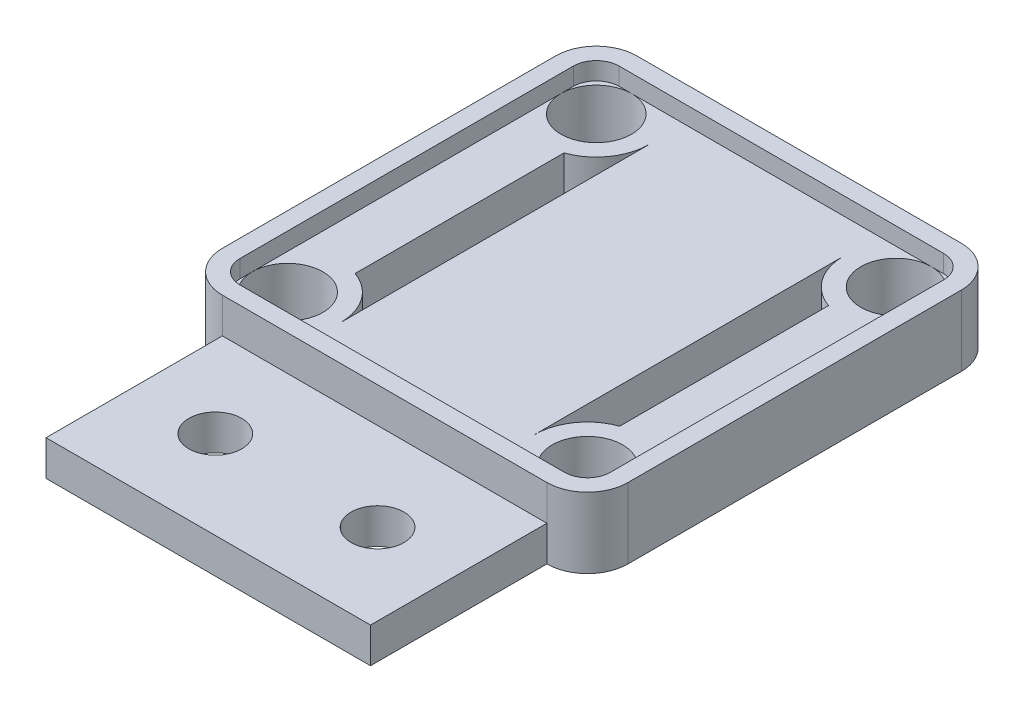
SolidWorks part; units mm, degrees
ref_plane "Front Plane" through (0, 0, 0) normal (0, 0, 1) x (1, 0, 0)
ref_plane "Top Plane" through (0, 0, 0) normal (0, 1, 0) x (1, 0, 0)
ref_plane "Right Plane" through (0, 0, 0) normal (1, 0, 0) x (0, 0, -1)
sketch "Sketch1" plane through (0, 0, 0) normal (0, 1, 0) x (1, 0, 0)
  line L1 (-12.6491, 14.6331) -> (5.7509, 14.6331)
  line L2 (-14.9491, 12.3331) -> (-14.9491, -6.5669)
  line L3 (-12.6491, -8.8669) -> (5.7509, -8.8669)
  line L4 (8.0509, 12.3331) -> (8.0509, -6.5669)
  line L5 (-14.9491, 14.6331) -> (8.0509, -8.8669) construction
  line L6 (-14.9491, -8.8669) -> (8.0509, 14.6331) construction
  arc A0 (8.0509, 12.3331) -> (5.7509, 14.6331) centre (5.7509, 12.3331) ccw
  arc A1 (-12.6491, -8.8669) -> (-14.9491, -6.5669) centre (-12.6491, -6.5669) cw
  arc A2 (5.7509, -8.8669) -> (8.0509, -6.5669) centre (5.7509, -6.5669) ccw
  arc A3 (-14.9491, 12.3331) -> (-12.6491, 14.6331) centre (-12.6491, 12.3331) cw
  point P0 (-3.4491, 2.8831)
  dimension "D3" = 2.3
  dimension "D4" = 2.3
  dimension "D1" = 23.5
  dimension "D2" = 23
extrude "Boss-Extrude1" add sketch "Sketch1" along normal blind 4
sketch "Sketch2" plane through (0, 4, 0) normal (0, 1, 0) x (1, 0, 0)
  line L8 (5.7509, 13.6331) -> (-12.6491, 13.6331)
  line L9 (-13.9491, 12.3331) -> (-13.9491, -6.5669)
  line L10 (-12.6491, -7.8669) -> (5.7509, -7.8669)
  line L11 (7.0509, -6.5669) -> (7.0509, 12.3331)
  line L12 (5.7509, 13.6331) -> (-12.6491, 13.6331)
  line L13 (-13.9491, 12.3331) -> (-13.9491, -6.5669)
  line L14 (-12.6491, -7.8669) -> (5.7509, -7.8669)
  line L15 (7.0509, -6.5669) -> (7.0509, 12.3331)
  arc A8 (7.0509, 12.3331) -> (5.7509, 13.6331) centre (5.7509, 12.3331) ccw
  arc A9 (-12.6491, 13.6331) -> (-13.9491, 12.3331) centre (-12.6491, 12.3331) ccw
  arc A10 (-13.9491, -6.5669) -> (-12.6491, -7.8669) centre (-12.6491, -6.5669) ccw
  arc A11 (5.7509, -7.8669) -> (7.0509, -6.5669) centre (5.7509, -6.5669) ccw
  arc A12 (7.0509, 12.3331) -> (5.7509, 13.6331) centre (5.7509, 12.3331) ccw
  arc A13 (-12.6491, 13.6331) -> (-13.9491, 12.3331) centre (-12.6491, 12.3331) ccw
  arc A14 (-13.9491, -6.5669) -> (-12.6491, -7.8669) centre (-12.6491, -6.5669) ccw
  arc A15 (5.7509, -7.8669) -> (7.0509, -6.5669) centre (5.7509, -6.5669) ccw
  dimension "D1" = 1
extrude "Cut-Extrude2" cut sketch "Sketch2" against normal blind 1
sketch "Sketch5" plane through (0, 3, 0) normal (0, 1, 0) x (1, 0, 0)
  line L0 (-3.4491, 13.6331) -> (-3.4491, -7.8669) construction
  line L1 (5.7509, 13.6331) -> (-12.6491, 13.6331) construction
  line L2 (-12.6491, -7.8669) -> (5.7509, -7.8669) construction
  line L3 (7.0509, 2.8831) -> (-13.9491, 2.8831) construction
  line L4 (7.0509, -6.5669) -> (7.0509, 12.3331) construction
  line L5 (-13.9491, 12.3331) -> (-13.9491, -6.5669) construction
  circle A0 centre (5.0509, 11.6331) radius 2
  circle A1 centre (5.0509, -5.8669) radius 2
  circle A2 centre (-11.9491, -5.8669) radius 2
  circle A3 centre (-11.9491, 11.6331) radius 2
  point P16 (0, 0)
  dimension "D1" = 4
extrude "Cut-Extrude3" cut sketch "Sketch5" against normal through all
sketch "Sketch6" plane through (0, 3, 0) normal (0, 1, 0) x (1, 0, 0)
  line L0 (-14.9491, 12.3331) -> (-14.9491, -6.5669) construction
  line L1 (8.0509, -6.5669) -> (8.0509, 12.3331) construction
  line L14 (4.0509, -5.8669) -> (4.0509, 11.6331)
  line L15 (4.0509, -3.0385) -> (4.0509, 8.8047)
  line L16 (2.0509, 11.6331) -> (2.0509, -5.8669)
  line L17 (-10.9491, 12.3331) -> (-10.9491, -6.5669)
  line L18 (-10.9491, 8.8047) -> (-10.9491, -3.0385)
  line L19 (-8.9491, 11.6331) -> (-8.9491, -5.8669)
  arc A5 (-11.9491, -8.8669) -> (-14.9491, -5.8669) centre (-11.9491, -5.8669) ccw
  arc A6 (-8.9491, -5.8669) -> (-10.9491, -3.0385) centre (-11.9491, -5.8669) ccw
  arc A20 (5.0509, 14.6331) -> (8.0509, 11.6331) centre (5.0509, 11.6331) ccw
  arc A21 (2.0509, 11.6331) -> (4.0509, 8.8047) centre (5.0509, 11.6331) ccw
  arc A23 (-14.9491, 11.6331) -> (-11.9491, 14.6331) centre (-11.9491, 11.6331) ccw
  arc A24 (-10.9491, 8.8047) -> (-8.9491, 11.6331) centre (-11.9491, 11.6331) ccw
  arc A26 (8.0509, -5.8669) -> (5.0509, -8.8669) centre (5.0509, -5.8669) ccw
  arc A27 (4.0509, -3.0385) -> (2.0509, -5.8669) centre (5.0509, -5.8669) ccw
  dimension "D1" = 23
  dimension "D2" = 1
  dimension "D3" = 1
  dimension "D4" = 1
  dimension "D5" = 1
  dimension "D6" = 3
  dimension "D7" = 3
extrude "Cut-Extrude4" cut sketch "Sketch6" against normal through all
sketch "Sketch7" plane through (0, 0, 8.8669) normal (0, 0, 1) x (1, 0, 0)
  line L0 (-14.9491, 4) -> (-14.9491, 0) construction
  line L1 (8.0509, 4) -> (8.0509, 0) construction
  line L2 (-12.6491, 4) -> (-12.6491, 0) construction
  line L3 (-12.6491, 2) -> (5.7509, 2)
  line L4 (5.7509, 4) -> (5.7509, 0) construction
  line L5 (5.7509, 2) -> (5.7509, 0)
  line L6 (5.7509, 0) -> (-12.6491, 0)
  line L7 (-12.6491, 0) -> (-12.6491, 2)
  dimension "D1" = 23
extrude "Boss-Extrude2" add sketch "Sketch7" along normal blind 10
sketch "Sketch8" plane through (0, 2, 0) normal (0, 1, 0) x (1, 0, 0)
  line L0 (-12.6491, -8.8669) -> (5.7509, -8.8669) construction
  line L1 (-12.6491, -18.8669) -> (-12.6491, -8.8669) construction
  line L2 (5.7509, -18.8669) -> (5.7509, -8.8669) construction
  line L3 (-3.4491, -8.8669) -> (-3.4491, -18.8669) construction
  line L4 (5.7509, -18.8669) -> (-12.6491, -18.8669) construction
  circle A0 centre (1.1509, -13.8669) radius 1.5
  circle A1 centre (-8.0491, -13.8669) radius 1.5
  point P4 (0, 0)
  point P15 (0, 0)
  point P16 (0, 0)
  dimension "D2" = 3
  dimension "D1" = 5
  dimension "D3" = 18.4
  dimension "D4" = 4.6
  dimension "D5" = 4.6
extrude "Cut-Extrude5" cut sketch "Sketch8" against normal through all
